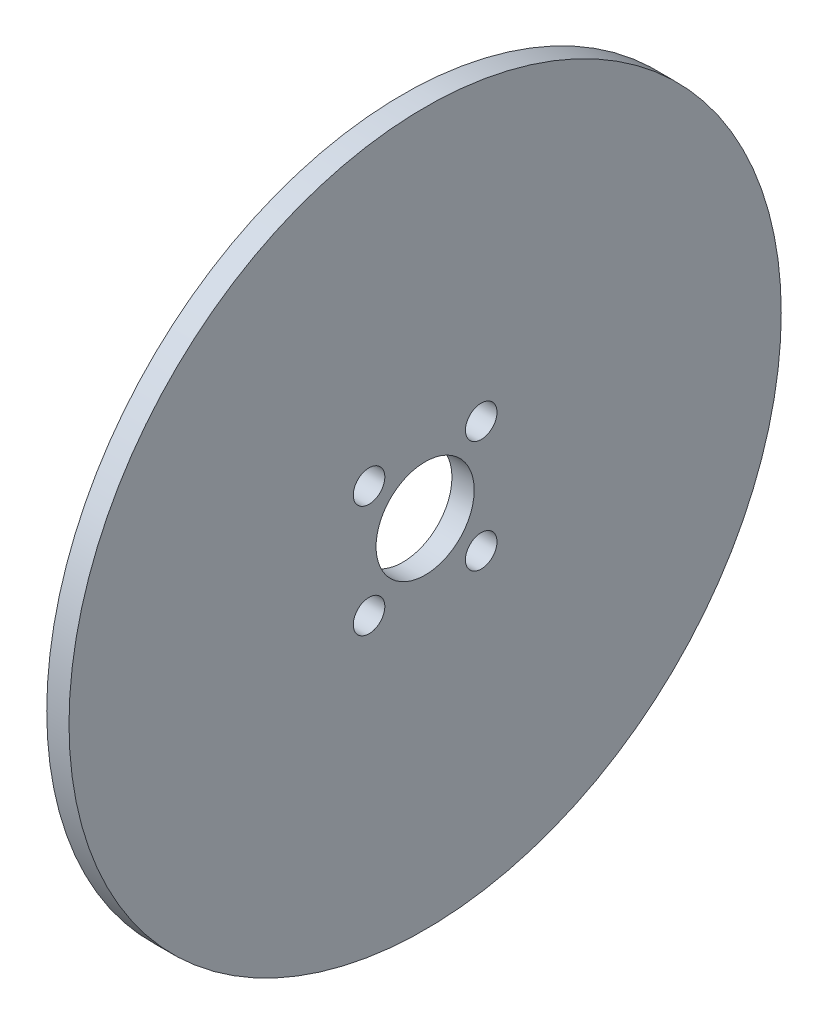
SolidWorks part; units mm, degrees
ref_plane "Front Plane" through (0, 0, 0) normal (1, 0, 0) x (0, 1, 0)
ref_plane "Top Plane" through (0, 0, 0) normal (0, 0, 1) x (0, 1, 0)
ref_plane "Right Plane" through (0, 0, 0) normal (0, 1, 0) x (-1, 0, 0)
sketch "Sketch1" plane through (0, 0, 0) normal (1, 0, 0) x (0, 1, 0)
  circle A0 centre (0, 0) radius 50.8
  circle A1 centre (0, 0) radius 7
  dimension "D1" = 101.6
  dimension "D2" = 14
extrude "Boss-Extrude2" add sketch "Sketch1" along normal blind 3.175
sketch "Sketch2" plane through (3.175, 0, 0) normal (1, 0, 0) x (0, 1, 0)
  line L1 (8, -8) -> (-8, -8) construction
  line L2 (8, -8) -> (8, 8) construction
  line L3 (8, 8) -> (-8, 8) construction
  line L4 (-8, -8) -> (-8, 8) construction
  line L5 (8, -8) -> (-8, 8) construction
  line L6 (8, 8) -> (-8, -8) construction
  line L7 (12.7, -12.7) -> (-12.7, -12.7) construction
  line L8 (12.7, -12.7) -> (12.7, 12.7) construction
  line L9 (12.7, 12.7) -> (-12.7, 12.7) construction
  line L10 (-12.7, -12.7) -> (-12.7, 12.7) construction
  line L11 (12.7, -12.7) -> (-12.7, 12.7) construction
  line L12 (12.7, 12.7) -> (-12.7, -12.7) construction
  circle A1 centre (-8, 8) radius 2.25
  circle A2 centre (8, 8) radius 2.25
  circle A3 centre (8, -8) radius 2.25
  circle A4 centre (-8, -8) radius 2.25
  circle A5 centre (0, 0) radius 20.574 construction
  dimension "D2" = 4.5
  dimension "D5" = 41.148
  dimension "D3" = 16
  dimension "D4" = 25.4
extrude "Cut-Extrude1" cut sketch "Sketch2" against normal blind 3.175
